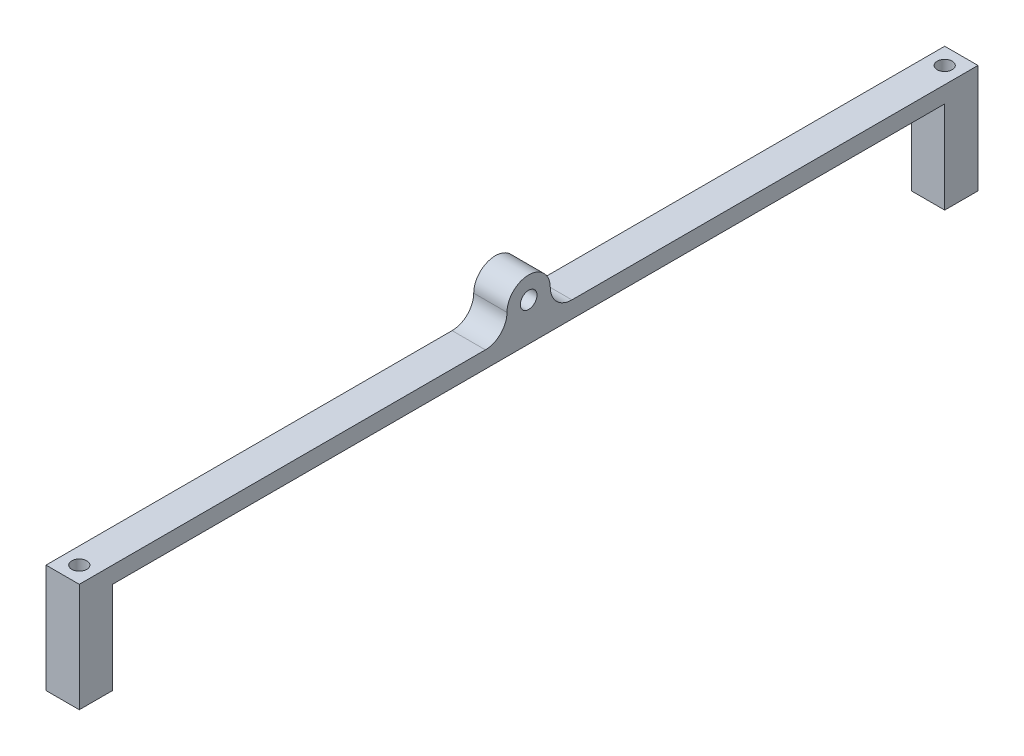
SolidWorks part; units mm, degrees
ref_plane "Спереди" through (0, 0, 0) normal (0, 0, 1) x (1, 0, 0)
ref_plane "Сверху" through (0, 0, 0) normal (0, 1, 0) x (1, 0, 0)
ref_plane "Справа" through (0, 0, 0) normal (1, 0, 0) x (0, 0, -1)
other "Configuration Table"
sketch "Эскиз1" plane through (0, 0, 0) normal (0, 1, 0) x (1, 0, 0)
  line L1 (0, 270) -> (10, 270)
  line L2 (0, 270) -> (0, 0)
  line L3 (0, 0) -> (10, 0)
  line L4 (10, 270) -> (10, 0)
  line L5 (342.3, 270) -> (342.3, 0) construction
  line L7 (0, 260) -> (10, 270) construction
  line L10 (0, 260) -> (10, 260) construction
  line L14 (0, 10) -> (10, 10) construction
  line L16 (0, 270) -> (10, 260) construction
  line L17 (0, 10) -> (10, 0) construction
  line L18 (10, 10) -> (0, 0) construction
  circle A0 centre (5, 265) radius 2.25
  circle A1 centre (5, 5) radius 2.25
  dimension "D5" = 4.5
  dimension "D6" = 4.5
  dimension "D2" = 10
  dimension "D3" = 10
  dimension "D4" = 10
extrude "Бобышка-Вытянуть1" add sketch "Эскиз1" along normal blind 5
sketch "Эскиз2" plane through (0, 0, 0) normal (1, 0, 0) x (0, 0, -1)
  line L0 (128.5, 11.5) -> (141.5, 11.5) construction
  line L1 (122, 5) -> (148, 5)
  line L2 (0, 5) -> (270, 5) construction
  arc A0 (141.5, 11.5) -> (128.5, 11.5) centre (135, 11.5) ccw
  arc A2 (122, 5) -> (128.5, 11.5) centre (122, 11.5) ccw
  arc A3 (141.5, 11.5) -> (148, 5) centre (148, 11.5) ccw
  circle A4 centre (135, 11.5) radius 2.5
  point P1 (135, 5)
  point P5 (135, 5)
  point P6 (141.5, 11.5)
  point P7 (128.5, 11.5)
  dimension "D1" = 13
  dimension "D2" = 13
  dimension "D3" = 13
  dimension "D4" = 5
extrude "Бобышка-Вытянуть2" add sketch "Эскиз2" along normal blind 10
sketch "Эскиз3" plane through (0, 0, 0) normal (0, -1, 0) x (1, 0, 0)
  line L0 (10, 0) -> (10, -270) construction
  line L1 (0, 0) -> (10, 0)
  line L2 (0, 0) -> (0, -10)
  line L3 (0, -10) -> (10, -10)
  line L4 (10, 0) -> (10, -10)
  line L6 (0, -270) -> (10, -270)
  line L7 (0, -270) -> (0, -260)
  line L8 (0, -260) -> (10, -260)
  line L9 (10, -270) -> (10, -260)
  circle A526 centre (5, -265) radius 2.25
  circle A527 centre (5, -265) radius 2.25
  circle A529 centre (5, -5) radius 2.25
  circle A530 centre (5, -5) radius 2.25
  dimension "D1" = 10
  dimension "D2" = 10
  dimension "D3" = 0
  dimension "D4" = 0
extrude "Бобышка-Вытянуть3" add sketch "Эскиз3" along normal up to surface (27.65 mm away)
